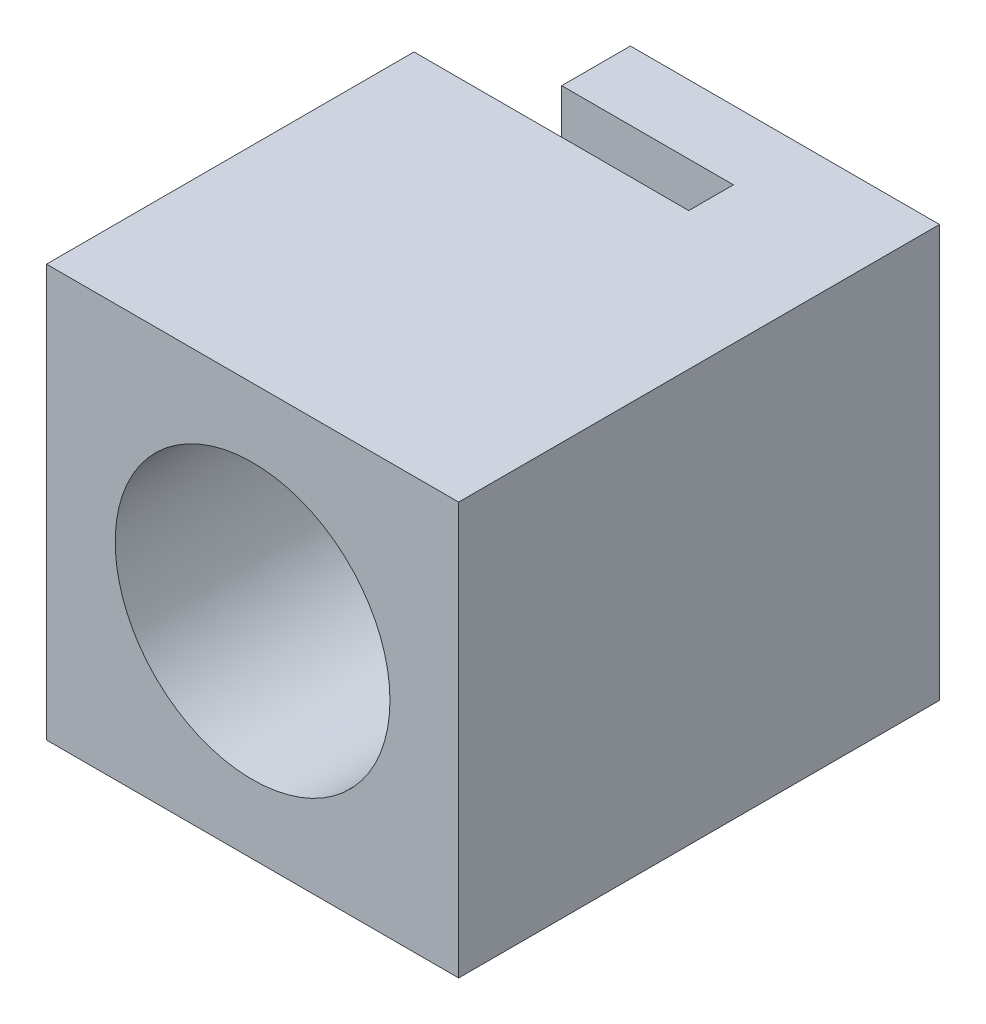
SolidWorks part; units mm, degrees
ref_plane "Plan de face" through (0, 0, 0) normal (0, 0, 1) x (1, 0, 0)
ref_plane "Plan de dessus" through (0, 0, 0) normal (0, 1, 0) x (1, 0, 0)
ref_plane "Plan de droite" through (0, 0, 0) normal (1, 0, 0) x (0, 0, -1)
sketch "Esquisse1" plane through (0, 0, 0) normal (0, 0, 1) x (1, 0, 0)
  line L1 (-6, 6) -> (6, 6)
  line L2 (-6, 6) -> (-6, -6)
  line L3 (-6, -6) -> (6, -6)
  line L4 (6, 6) -> (6, -6)
  line L5 (-6, 6) -> (6, -6) construction
  line L6 (-6, -6) -> (6, 6) construction
  point P0 (0, 0)
  dimension "D1" = 12
  dimension "D2" = 12
extrude "Boss.-Extru.1" add sketch "Esquisse1" along normal blind 14
sketch "Esquisse2" plane through (0, 0, 14) normal (0, 0, 1) x (1, 0, 0)
  circle A0 centre (0, 0) radius 4
  dimension "D1" = 8
extrude "Enlèv. mat.-Extru.1" cut sketch "Esquisse2" against normal blind 6 contours A0
ref_plane "Plan1" through (-16, 0, 0) normal (-1, 0, 0) x (0, 0, 1)
sketch "Esquisse3" plane through (-16, 0, 0) normal (-1, 0, 0) x (0, 0, 1)
  line L0 (0, 6) -> (0, -6) construction
  line L1 (2, -7.1483) -> (3.3, -7.1483)
  line L2 (2, -7.1483) -> (2, 7.1483)
  line L3 (2, 7.1483) -> (3.3, 7.1483)
  line L4 (3.3, -7.1483) -> (3.3, 7.1483)
  line L5 (2, -7.1483) -> (3.3, 7.1483) construction
  line L6 (2, 7.1483) -> (3.3, -7.1483) construction
  point P0 (2.65, 0)
  dimension "D1" = 2
  dimension "D2" = 1.3
extrude "Enlèv. mat.-Extru.2" cut sketch "Esquisse3" against normal blind 18
sketch "Esquisse5" plane through (0, 0, 0) normal (1, 0, 0) x (0, 0, -1)
  line L0 (0.4217, 6.3255) -> (-2.2352, 6.3255)
  line L1 (0.4217, 6.3255) -> (0.4217, -6.4839)
  line L2 (-2.2352, 6.3255) -> (-2.2352, -6.4839)
  line L3 (0.4217, -6.4839) -> (-2.2352, -6.4839)
sketch "Esquisse6" plane through (-16, 0, 0) normal (-1, 0, 0) x (0, 0, 1)
  line L0 (-0.4217, 6.3255) -> (2.2352, 6.3255)
  line L1 (-0.4217, 6.3255) -> (-0.4217, -6.4663)
  line L2 (2.2352, 6.3255) -> (2.2352, -6.4663)
  line L3 (-0.4217, -6.4663) -> (2.2352, -6.4663)
extrude "Enlèv. mat.-Extru.4" cut sketch "Esquisse6" against normal blind 13
